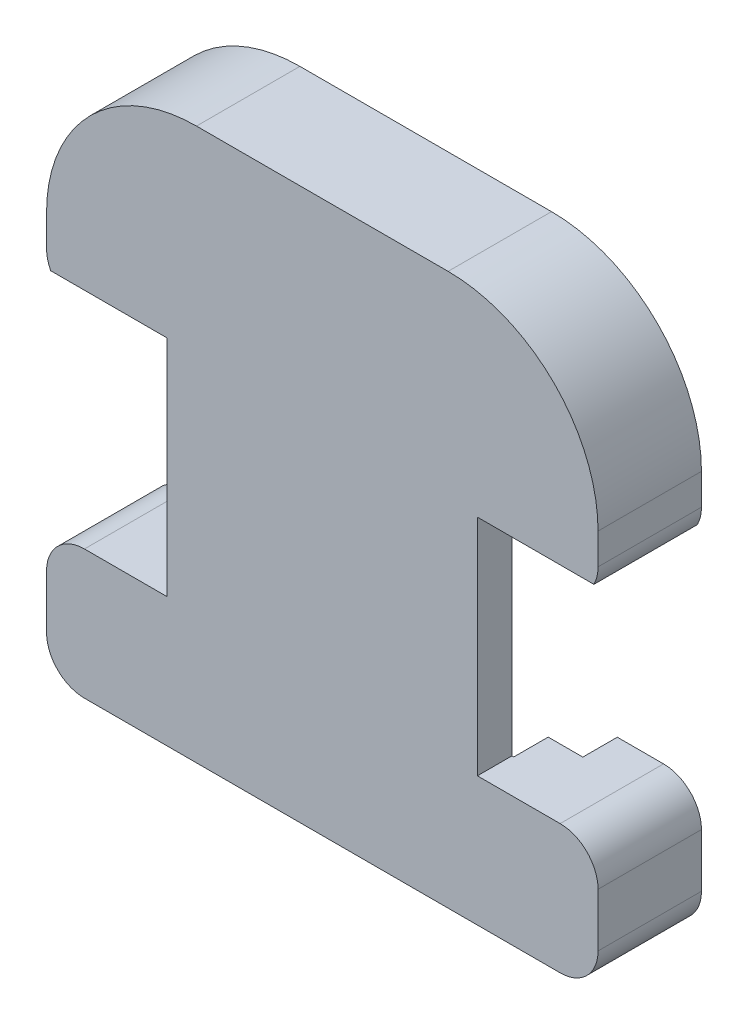
SolidWorks part; units mm, degrees
ref_plane "Front Plane" through (0, 0, 0) normal (0, 0, 1) x (1, 0, 0)
ref_plane "Top Plane" through (0, 0, 0) normal (0, 1, 0) x (1, 0, 0)
ref_plane "Right Plane" through (0, 0, 0) normal (1, 0, 0) x (0, 0, -1)
ref_plane "Plane1" through (0, 0, 2.54) normal (0, 0, 1) x (1, 0, 0)
sketch "Sketch1" plane through (0, 0, 2.54) normal (0, 0, 1) x (1, 0, 0)
  line L0 (-35.052, 0) -> (35.052, 0)
  line L1 (38.1, 3.048) -> (38.1, 10.922)
  line L2 (35.052, 13.97) -> (31.242, 13.97)
  line L3 (28.194, 17.018) -> (28.194, 45.974)
  line L4 (31.242, 49.022) -> (35.052, 49.022)
  line L5 (38.1, 52.07) -> (38.1, 56.642)
  line L6 (18.542, 76.2) -> (-18.542, 76.2)
  line L7 (-38.1, 56.642) -> (-38.1, 52.07)
  line L8 (-35.052, 49.022) -> (-31.242, 49.022)
  line L9 (-28.194, 45.974) -> (-28.194, 17.018)
  line L10 (-31.242, 13.97) -> (-35.052, 13.97)
  line L11 (-38.1, 10.922) -> (-38.1, 3.048)
  arc A0 (35.052, 49.022) -> (38.1, 52.07) centre (35.052, 52.07) ccw
  arc A1 (-38.1, 52.07) -> (-35.052, 49.022) centre (-35.052, 52.07) ccw
  arc A2 (-31.242, 49.022) -> (-28.194, 45.974) centre (-31.242, 45.974) cw
  arc A3 (28.194, 45.974) -> (31.242, 49.022) centre (31.242, 45.974) cw
  arc A4 (38.1, 10.922) -> (35.052, 13.97) centre (35.052, 10.922) ccw
  arc A5 (31.242, 13.97) -> (28.194, 17.018) centre (31.242, 17.018) cw
  arc A6 (-28.194, 17.018) -> (-31.242, 13.97) centre (-31.242, 17.018) cw
  arc A7 (-35.052, 13.97) -> (-38.1, 10.922) centre (-35.052, 10.922) ccw
  arc A8 (-35.052, 0) -> (-38.1, 3.048) centre (-35.052, 3.048) cw
  arc A9 (35.052, 0) -> (38.1, 3.048) centre (35.052, 3.048) ccw
  arc A10 (-18.542, 76.2) -> (-38.1, 56.642) centre (-18.542, 56.642) ccw
  arc A11 (38.1, 56.642) -> (18.542, 76.2) centre (18.542, 56.642) ccw
  dimension "D1" = 3.048
  dimension "D4" = 76.2
  dimension "D5" = 76.2
  dimension "D6" = 28.956
  dimension "D7" = 7.874
  dimension "D8" = 9.906
  dimension "D2" = 19.558
extrude "Boss-Extrude1" add sketch "Sketch1" against normal blind 10.16
sketch "Sketch2" plane through (0, 0, -7.62) normal (0, 0, -1) x (-1, 0, 0)
  line L12 (33.02, 54.102) -> (33.02, 56.642)
  line L13 (33.02, 54.102) -> (33.02, 56.642)
  line L14 (-33.02, 56.642) -> (-33.02, 54.102)
  line L15 (-33.02, 56.642) -> (-33.02, 54.102)
  line L24 (-33.02, 54.102) -> (-31.242, 54.102)
  line L25 (-23.114, 45.974) -> (-23.114, 17.018)
  line L26 (-31.242, 8.89) -> (-33.02, 8.89)
  line L27 (-33.02, 8.89) -> (-33.02, 5.08)
  line L28 (-33.02, 5.08) -> (33.02, 5.08)
  line L29 (33.02, 5.08) -> (33.02, 8.89)
  line L30 (33.02, 8.89) -> (31.242, 8.89)
  line L31 (23.114, 17.018) -> (23.114, 45.974)
  line L32 (31.242, 54.102) -> (33.02, 54.102)
  line L34 (18.542, 71.12) -> (-18.542, 71.12)
  line L36 (-33.02, 54.102) -> (-31.242, 54.102)
  line L37 (-23.114, 45.974) -> (-23.114, 17.018)
  line L38 (-31.242, 8.89) -> (-33.02, 8.89)
  line L39 (-33.02, 8.89) -> (-33.02, 5.08)
  line L40 (-33.02, 5.08) -> (33.02, 5.08)
  line L41 (33.02, 5.08) -> (33.02, 8.89)
  line L42 (33.02, 8.89) -> (31.242, 8.89)
  line L43 (23.114, 17.018) -> (23.114, 45.974)
  line L44 (31.242, 54.102) -> (33.02, 54.102)
  line L46 (18.542, 71.12) -> (-18.542, 71.12)
  arc A24 (-23.114, 45.974) -> (-31.242, 54.102) centre (-31.242, 45.974) ccw
  arc A25 (-31.242, 8.89) -> (-23.114, 17.018) centre (-31.242, 17.018) ccw
  arc A26 (23.114, 17.018) -> (31.242, 8.89) centre (31.242, 17.018) ccw
  arc A27 (31.242, 54.102) -> (23.114, 45.974) centre (31.242, 45.974) ccw
  arc A28 (33.02, 56.642) -> (18.542, 71.12) centre (18.542, 56.642) ccw
  arc A29 (-18.542, 71.12) -> (-33.02, 56.642) centre (-18.542, 56.642) ccw
  arc A30 (-23.114, 45.974) -> (-31.242, 54.102) centre (-31.242, 45.974) ccw
  arc A31 (-31.242, 8.89) -> (-23.114, 17.018) centre (-31.242, 17.018) ccw
  arc A32 (23.114, 17.018) -> (31.242, 8.89) centre (31.242, 17.018) ccw
  arc A33 (31.242, 54.102) -> (23.114, 45.974) centre (31.242, 45.974) ccw
  arc A34 (33.02, 56.642) -> (18.542, 71.12) centre (18.542, 56.642) ccw
  arc A35 (-18.542, 71.12) -> (-33.02, 56.642) centre (-18.542, 56.642) ccw
  dimension "D1" = 5.08
extrude "Cut-Extrude1" cut sketch "Sketch2" against normal blind 5.08
sketch "Sketch7" plane through (0, 0, -7.62) normal (0, 0, -1) x (-1, 0, 0)
  line L24 (-35.052, 46.482) -> (-31.242, 46.482)
  line L25 (-30.734, 45.974) -> (-30.734, 17.018)
  line L26 (-31.242, 16.51) -> (-35.052, 16.51)
  line L27 (-40.64, 10.922) -> (-40.64, 3.048)
  line L28 (-35.052, -2.54) -> (35.052, -2.54)
  line L29 (40.64, 3.048) -> (40.64, 10.922)
  line L30 (35.052, 16.51) -> (31.242, 16.51)
  line L31 (30.734, 17.018) -> (30.734, 45.974)
  line L32 (31.242, 46.482) -> (35.052, 46.482)
  line L33 (40.64, 52.07) -> (40.64, 56.642)
  line L34 (18.542, 78.74) -> (-18.542, 78.74)
  line L35 (-40.64, 56.642) -> (-40.64, 52.07)
  line L36 (-35.052, 46.482) -> (-31.242, 46.482)
  line L37 (-30.734, 45.974) -> (-30.734, 17.018)
  line L38 (-31.242, 16.51) -> (-35.052, 16.51)
  line L39 (-40.64, 10.922) -> (-40.64, 3.048)
  line L40 (-35.052, -2.54) -> (35.052, -2.54)
  line L41 (40.64, 3.048) -> (40.64, 10.922)
  line L42 (35.052, 16.51) -> (31.242, 16.51)
  line L43 (30.734, 17.018) -> (30.734, 45.974)
  line L44 (31.242, 46.482) -> (35.052, 46.482)
  line L45 (40.64, 52.07) -> (40.64, 56.642)
  line L46 (18.542, 78.74) -> (-18.542, 78.74)
  line L47 (-40.64, 56.642) -> (-40.64, 52.07)
  arc A12 (40.64, 56.642) -> (18.542, 78.74) centre (18.542, 56.642) ccw
  arc A13 (40.64, 56.642) -> (18.542, 78.74) centre (18.542, 56.642) ccw
  arc A18 (-18.542, 78.74) -> (-40.64, 56.642) centre (-18.542, 56.642) ccw
  arc A19 (-18.542, 78.74) -> (-40.64, 56.642) centre (-18.542, 56.642) ccw
  arc A24 (-40.64, 52.07) -> (-35.052, 46.482) centre (-35.052, 52.07) ccw
  arc A25 (-30.734, 45.974) -> (-31.242, 46.482) centre (-31.242, 45.974) ccw
  arc A26 (-31.242, 16.51) -> (-30.734, 17.018) centre (-31.242, 17.018) ccw
  arc A27 (-35.052, 16.51) -> (-40.64, 10.922) centre (-35.052, 10.922) ccw
  arc A28 (-40.64, 3.048) -> (-35.052, -2.54) centre (-35.052, 3.048) ccw
  arc A29 (35.052, -2.54) -> (40.64, 3.048) centre (35.052, 3.048) ccw
  arc A30 (40.64, 10.922) -> (35.052, 16.51) centre (35.052, 10.922) ccw
  arc A31 (30.734, 17.018) -> (31.242, 16.51) centre (31.242, 17.018) ccw
  arc A32 (31.242, 46.482) -> (30.734, 45.974) centre (31.242, 45.974) ccw
  arc A33 (35.052, 46.482) -> (40.64, 52.07) centre (35.052, 52.07) ccw
  arc A36 (-40.64, 52.07) -> (-35.052, 46.482) centre (-35.052, 52.07) ccw
  arc A37 (-30.734, 45.974) -> (-31.242, 46.482) centre (-31.242, 45.974) ccw
  arc A38 (-31.242, 16.51) -> (-30.734, 17.018) centre (-31.242, 17.018) ccw
  arc A39 (-35.052, 16.51) -> (-40.64, 10.922) centre (-35.052, 10.922) ccw
  arc A40 (-40.64, 3.048) -> (-35.052, -2.54) centre (-35.052, 3.048) ccw
  arc A41 (35.052, -2.54) -> (40.64, 3.048) centre (35.052, 3.048) ccw
  arc A42 (40.64, 10.922) -> (35.052, 16.51) centre (35.052, 10.922) ccw
  arc A43 (30.734, 17.018) -> (31.242, 16.51) centre (31.242, 17.018) ccw
  arc A44 (31.242, 46.482) -> (30.734, 45.974) centre (31.242, 45.974) ccw
  arc A45 (35.052, 46.482) -> (40.64, 52.07) centre (35.052, 52.07) ccw
  arc M47 (-38.1, 52.07) -> (-35.052, 49.022) centre (-35.052, 52.07) ccw
  line M48 (-35.052, 49.022) -> (-31.242, 49.022)
  arc M49 (-31.242, 49.022) -> (-28.194, 45.974) centre (-31.242, 45.974) cw
  line M50 (-28.194, 45.974) -> (-28.194, 17.018)
  arc M51 (-28.194, 17.018) -> (-31.242, 13.97) centre (-31.242, 17.018) cw
  line M52 (-31.242, 13.97) -> (-35.052, 13.97)
  arc M53 (-35.052, 13.97) -> (-38.1, 10.922) centre (-35.052, 10.922) ccw
  line M54 (-38.1, 10.922) -> (-38.1, 3.048)
  arc M55 (-38.1, 3.048) -> (-35.052, 0) centre (-35.052, 3.048) ccw
  line M56 (-35.052, 0) -> (35.052, 0)
  arc M57 (35.052, 0) -> (38.1, 3.048) centre (35.052, 3.048) ccw
  line M58 (38.1, 3.048) -> (38.1, 10.922)
  arc M59 (38.1, 10.922) -> (35.052, 13.97) centre (35.052, 10.922) ccw
  line M60 (35.052, 13.97) -> (31.242, 13.97)
  arc M61 (31.242, 13.97) -> (28.194, 17.018) centre (31.242, 17.018) cw
  line M62 (28.194, 17.018) -> (28.194, 45.974)
  arc M63 (28.194, 45.974) -> (31.242, 49.022) centre (31.242, 45.974) cw
  line M64 (31.242, 49.022) -> (35.052, 49.022)
  arc M65 (35.052, 49.022) -> (38.1, 52.07) centre (35.052, 52.07) ccw
  line M66 (38.1, 52.07) -> (38.1, 56.642)
  arc M67 (38.1, 56.642) -> (18.542, 76.2) centre (18.542, 56.642) ccw
  line M68 (18.542, 76.2) -> (-18.542, 76.2)
  arc M69 (-18.542, 76.2) -> (-38.1, 56.642) centre (-18.542, 56.642) ccw
  line M70 (-38.1, 56.642) -> (-38.1, 52.07)
  dimension "D1" = 2.54
extrude "Boss-Extrude2" add sketch "Sketch7" along normal blind 5.08 and the other way up to surface (10.16 mm away) contours L46 A19 L47 A36 L36 A37 L37 A38 L38 A39 L39 A40 L40 A41 L41 A42 L42 A43 L43 A44 L44 A45 L45 A13 M47 M70 M69 M68 M67 M66 M65 M64 M63 M62 M61 M60 M59 M58 M57 M56 M55 M54 M53 M52 M51 M50 M49 M48 other way up to face at (0, 32.6064, 2.54)
sketch "Sketch8" plane through (0, 0, -12.7) normal (0, 0, -1) x (-1, 0, 0)
  line L9 (-22.86, 49.53) -> (-22.86, 16.51)
  line L18 (-22.86, 49.53) -> (-46.482, 49.53)
  line L19 (-46.482, 49.53) -> (-46.482, 16.51)
  line L20 (-46.482, 16.51) -> (-22.86, 16.51)
  line L27 (0, 8.382) -> (0, -8.382) construction
  line L28 (46.482, 16.51) -> (22.86, 16.51)
  line L30 (22.86, 49.53) -> (22.86, 16.51)
  line L31 (22.86, 49.53) -> (46.482, 49.53)
  line L32 (46.482, 49.53) -> (46.482, 16.51)
  line L33 (-38.1, 10.922) -> (-38.1, 3.048) construction
  line L34 (-35.052, 0) -> (35.052, 0) construction
  dimension "D1" = 23.622
  dimension "D2" = 33.02
  dimension "D3" = 15.24
  dimension "D4" = 16.51
extrude "Cut-Extrude2" cut sketch "Sketch8" against normal up to surface (15.24 mm away) up to face at (0, 32.6064, 2.54)
